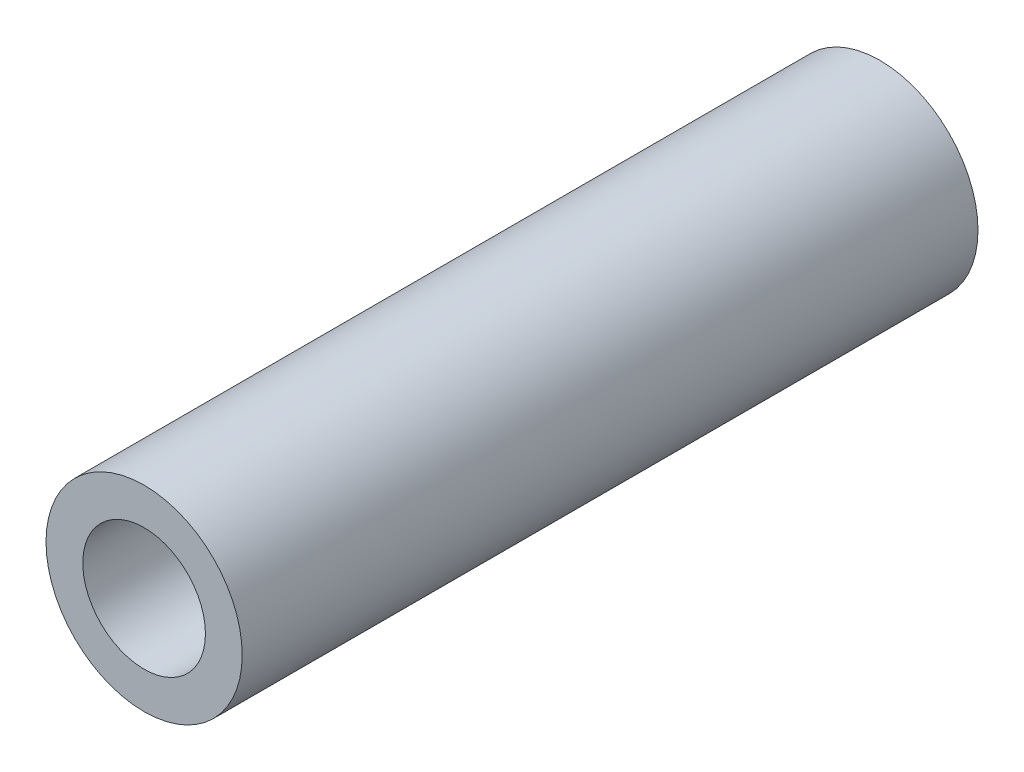
SolidWorks part; units mm, degrees
ref_plane "Front Plane" through (0, 0, 0) normal (0, 0, 1) x (1, 0, 0)
ref_plane "Top Plane" through (0, 0, 0) normal (0, 1, 0) x (1, 0, 0)
ref_plane "Right Plane" through (0, 0, 0) normal (1, 0, 0) x (0, 0, -1)
sketch "Sketch1" plane through (0, 0, 0) normal (0, 0, 1) x (1, 0, 0)
  circle A0 centre (0, 0) radius 8.7313
  circle A2 centre (0, 0) radius 12.7
  dimension "D1" = 17.4625
  dimension "D2" = 25.4
extrude "Boss-Extrude1" add sketch "Sketch1" along normal blind 6.35
ref_plane "Plane1" through (0, 0, 71.4375) normal (0, 0, 1) x (1, 0, 0)
sketch "Sketch2" plane through (0, 0, 71.4375) normal (0, 0, 1) x (1, 0, 0)
  circle A0 centre (0, 0) radius 7.9375
  circle A1 centre (0, 0) radius 12.7
  dimension "D1" = 15.875
  dimension "D2" = 25.4
extrude "Boss-Extrude2" add sketch "Sketch2" along normal blind 23.8125 separate body
sketch "Sketch3" plane through (0, 0, 71.4375) normal (0, 0, -1) x (-1, 0, 0)
  circle A0 centre (0, 0) radius 4.7625
  dimension "D1" = 9.525
sketch "Sketch5" plane through (0, 0, 6.35) normal (0, 0, 1) x (1, 0, 0)
  circle A0 centre (0, 0) radius 12.7
sketch "Sketch6" plane through (0, 0, 6.35) normal (0, 0, 1) x (1, 0, 0)
  circle A0 centre (0, 0) radius 6.35
  dimension "D1" = 12.7
extrude "Boss-Extrude4" add sketch "Sketch5" along normal up to surface (65.0875 mm away) up to face at (12.7, 0, 71.4375)
loft "Cut-Loft1" cut profiles "Sketch6", "Sketch3"
